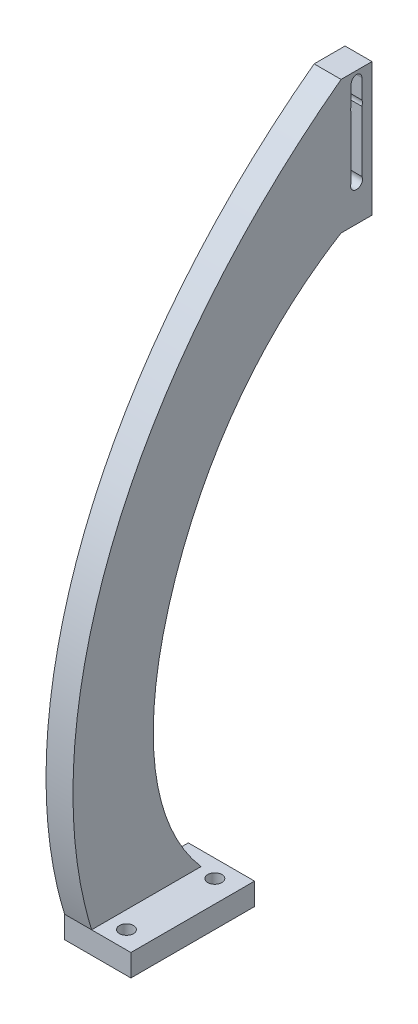
SolidWorks part; units mm, degrees
ref_plane "前视基准面" through (0, 0, 0) normal (0, 0, 1) x (1, 0, 0)
ref_plane "上视基准面" through (0, 0, 0) normal (0, 1, 0) x (1, 0, 0)
ref_plane "右视基准面" through (0, 0, 0) normal (1, 0, 0) x (0, 0, -1)
other "Configuration Table"
sketch "草图1" plane through (0, 0, 0) normal (0, 1, 0) x (1, 0, 0)
  line L0 (0, 0) -> (0, 10.0707) construction
  line L1 (-10, 14) -> (10, 14)
  line L2 (-10, 14) -> (-10, -14)
  line L3 (-10, -14) -> (10, -14)
  line L4 (10, 14) -> (10, -14)
  line L5 (-10, 14) -> (10, -14) construction
  line L6 (-10, -14) -> (10, 14) construction
  line L7 (0, 0) -> (4.3744, 0) construction
  circle A0 centre (-5, 10) radius 1.6
  circle A1 centre (5, 10) radius 1.6
  circle A2 centre (5, -10) radius 1.6
  circle A3 centre (-5, -10) radius 1.6
  point P0 (0, 0)
  dimension "D3" = 3.2
  dimension "D1" = 20
  dimension "D2" = 28
  dimension "D4" = 5
  dimension "D5" = 10
extrude "凸台-拉伸1" add sketch "草图1" along normal blind 5
sketch "草图2" plane through (0, 0, 0) normal (1, 0, 0) x (0, 0, -1)
  line L0 (42.4824, -6.5) -> (42.4824, 293.5) construction
  line L1 (-14, 5) -> (14, 5) construction
  line L2 (42.4824, 143.5) -> (42.4824, 113.3748)
  line L3 (-14, 5) -> (10.7943, 5)
  spline S0 degree 3 poles (-14, 5) (-21.091, 28.0724) (-16.0596, 83.5996) (19.3189, 126.3074) (42.4824, 143.5) knots 0 0 0 0 0.452387 1 1 1 1
  spline S1 degree 3 poles (10.7943, 5) (-3.6255, 21.7002) (-0.0389, 68.5305) (24.7866, 102.5635) (42.4824, 113.3748) knots 0 0 0 0 0.510479 1 1 1 1
extrude "凸台-拉伸2" add sketch "草图2" along normal blind 5 and the other way up to surface (1.1 mm away)
sketch "草图3" plane through (0, 0, -42.4824) normal (0, 0, -1) x (-1, 0, 0)
  line L4 (-5, 113.3748) -> (1.1, 113.3748)
  line L5 (1.1, 113.3748) -> (1.1, 143.5)
  line L6 (1.1, 143.5) -> (-5, 143.5)
  line L7 (-5, 143.5) -> (-5, 113.3748)
  line L8 (-5, 113.3748) -> (1.1, 113.3748)
  line L9 (1.1, 113.3748) -> (1.1, 143.5)
  line L10 (1.1, 143.5) -> (-5, 143.5)
  line L11 (-5, 143.5) -> (-5, 113.3748)
  dimension "D1" = 0
extrude "凸台-拉伸3" add sketch "草图3" along normal blind 7
sketch "草图4" plane through (5, 0, 0) normal (1, 0, 0) x (0, 0, -1)
  circle A0 centre (45.9824, 136.5) radius 1.35
  circle A1 centre (45.9824, 121.5) radius 1.35
  dimension "D1" = 2.7
extrude "切除-拉伸1" cut sketch "草图4" against normal blind 7
ref_plane "基准面1" through (20, 0, 0) normal (1, 0, 0) x (0, 0, -1)
mirror "镜向1" about plane through (20, 0, 0) normal (1, 0, 0) of bodies 109
delete or keep bodies "实体-删除/保留 1" type delete bodies bodies 109
sketch "草图5" plane through (0, 5, 0) normal (0, 1, 0) x (1, 0, 0)
  line L1 (30, 14) -> (35, 14)
  line L2 (30, 14) -> (30, -14)
  line L3 (30, -14) -> (35, -14)
  line L4 (35, 14) -> (35, -14)
extrude "切除-拉伸2" cut sketch "草图5" against normal blind 10
sketch "草图6" plane through (41.1, 0, 0) normal (1, 0, 0) x (0, 0, -1)
  line L0 (45.9824, 141.5) -> (45.9824, 121.5) construction
  line L1 (47.1824, 141.5) -> (47.1824, 121.5)
  line L2 (44.7824, 141.5) -> (44.7824, 121.5)
  arc A0 (47.1824, 141.5) -> (44.7824, 141.5) centre (45.9824, 141.5) ccw
  arc A1 (44.7824, 121.5) -> (47.1824, 121.5) centre (45.9824, 121.5) ccw
  point P4 (45.9824, 131.5)
  dimension "D1" = 1.2
  dimension "D2" = 20
extrude "切除-拉伸3" cut sketch "草图6" against normal blind 10
